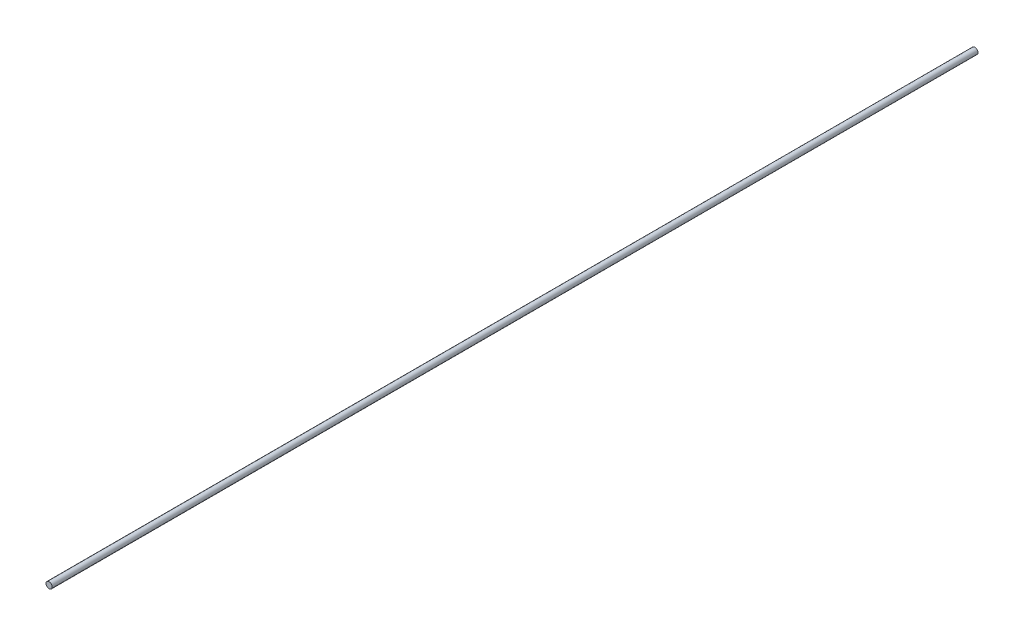
SolidWorks part; units mm, degrees
ref_plane "Front Plane" through (0, 0, 0) normal (0, 0, 1) x (1, 0, 0)
ref_plane "Top Plane" through (0, 0, 0) normal (0, 1, 0) x (1, 0, 0)
ref_plane "Right Plane" through (0, 0, 0) normal (1, 0, 0) x (0, 0, -1)
sketch "Sketch1" plane through (0, 0, 0) normal (0, 0, 1) x (1, 0, 0)
  circle A0 centre (0, 0) radius 0.5
  dimension "D1" = 1
extrude "Boss-Extrude1" add sketch "Sketch1" along normal blind 150
